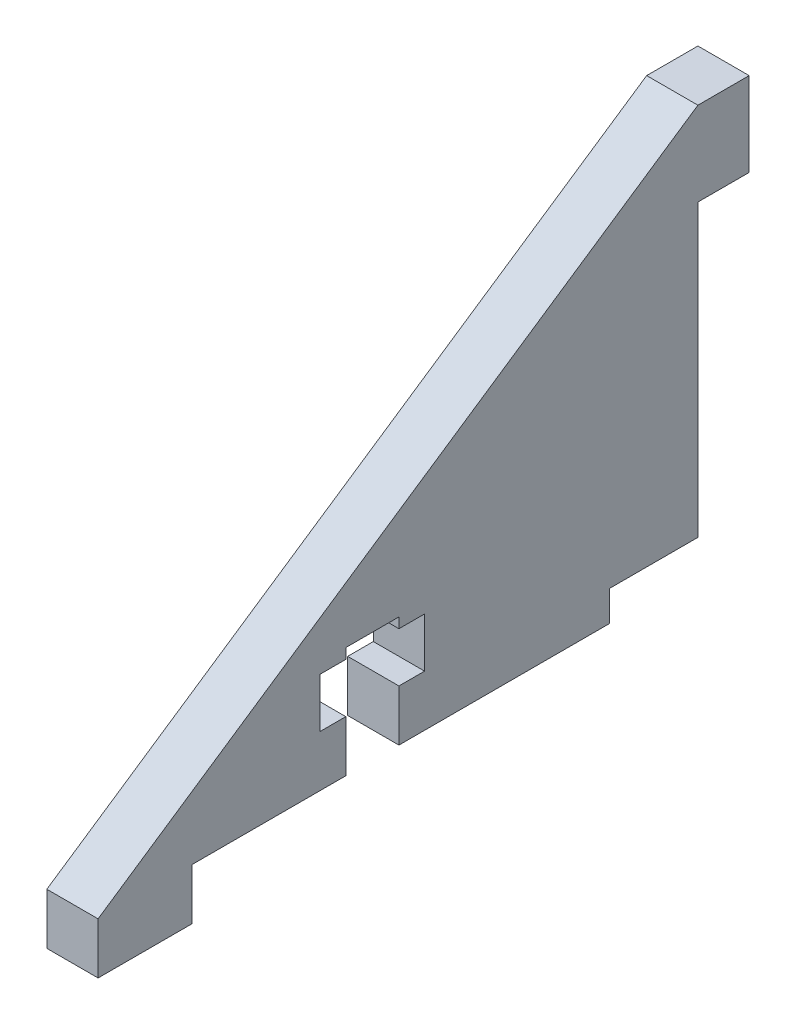
SolidWorks part; units mm, degrees
ref_plane "Alzado" through (0, 0, 0) normal (0, 0, 1) x (1, 0, 0)
ref_plane "Planta" through (0, 0, 0) normal (0, 1, 0) x (1, 0, 0)
ref_plane "Vista lateral" through (0, 0, 0) normal (1, 0, 0) x (0, 0, -1)
sketch "Croquis1" plane through (0, 0, 0) normal (1, 0, 0) x (0, 0, -1)
  line L0 (0, 0) -> (9, 0)
  line L1 (24.44, 0) -> (24.44, 1.78)
  line L2 (24.44, 1.78) -> (29.61, 1.78)
  line L3 (29.61, 1.78) -> (29.61, 18.78)
  line L4 (29.61, 18.78) -> (32.61, 18.78)
  line L5 (32.61, 18.78) -> (32.61, 23.69)
  line L6 (32.61, 23.69) -> (29.61, 23.69)
  line L7 (29.61, 23.69) -> (-5.5, 0)
  line L8 (-5.5, 0) -> (-5.5, -3)
  line L9 (-5.5, -3) -> (0, -3)
  line L10 (0, -3) -> (0, 0)
  line L12 (12.11, 0) -> (12.11, 3)
  line L13 (12.11, 3) -> (13.61, 3)
  line L14 (13.61, 3) -> (13.61, 5.9)
  line L15 (13.61, 5.9) -> (12.11, 5.9)
  line L16 (12.11, 5.9) -> (12.11, 6.5)
  line L17 (12.11, 6.5) -> (9, 6.5)
  line L18 (10.555, 0) -> (10.555, 6.5) construction
  line L19 (9, 5.9) -> (9, 6.5)
  line L20 (7.5, 5.9) -> (9, 5.9)
  line L21 (7.5, 3) -> (7.5, 5.9)
  line L22 (9, 3) -> (7.5, 3)
  line L23 (9, 0) -> (9, 3)
  line L24 (12.11, 0) -> (24.44, 0)
  dimension "D1" = 4.91
  dimension "D2" = 17
  dimension "D3" = 1.78
  dimension "D4" = 5.17
  dimension "D5" = 5.5
  dimension "D6" = 24.44
  dimension "D7" = 3
  dimension "D8" = 3
  dimension "D9" = 17.5
  dimension "D10" = 3
  dimension "D11" = 1.5
  dimension "D12" = 2.9
  dimension "D13" = 6.5
  dimension "D14" = 9
extrude "Saliente-Extruir1" add sketch "Croquis1" along normal blind 3
